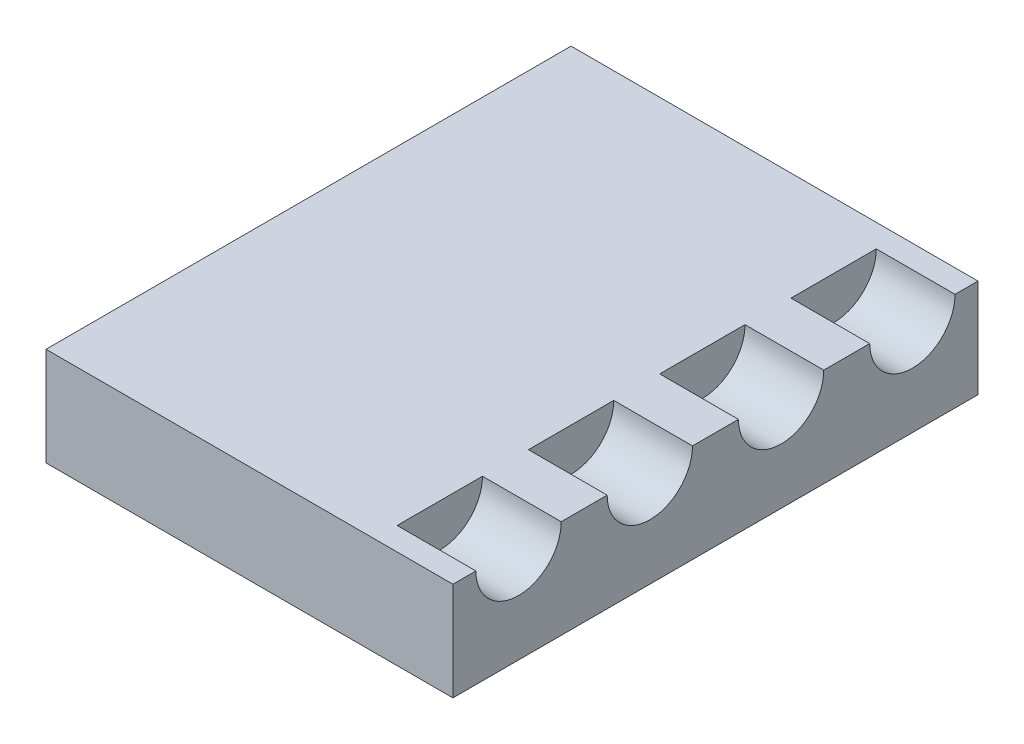
SolidWorks part; units mm, degrees
ref_plane "Front Plane" through (0, 0, 0) normal (0, 0, 1) x (1, 0, 0)
ref_plane "Top Plane" through (0, 0, 0) normal (0, 1, 0) x (1, 0, 0)
ref_plane "Right Plane" through (0, 0, 0) normal (1, 0, 0) x (0, 0, -1)
sketch "Sketch1" plane through (0, 0, 0) normal (1, 0, 0) x (0, 0, -1)
  line L0 (0, -8.0658) -> (0, 8.0658) construction
  line L1 (30, 0) -> (-30, 0) construction
  line L3 (-40, 0) -> (40, 0)
  line L4 (-40, 0) -> (-40, -15)
  line L5 (-40, -15) -> (40, -15)
  line L6 (40, 0) -> (40, -15)
  circle A0 centre (-30, 0) radius 6.5
  circle A1 centre (-10, 0) radius 6.5
  circle A2 centre (10, 0) radius 6.5
  circle A3 centre (30, 0) radius 6.5
  point P3 (10, 0)
  point P4 (0, 0)
  point P8 (0, 0)
  point P14 (-10, 0)
  point P19 (0, 0)
  dimension "D1" = 13
  dimension "D2" = 60
  dimension "D3" = 15
  dimension "D4" = 80
extrude "Boss-Extrude1" add sketch "Sketch1" along normal blind 12 contours A3 L3 A2 A1 A0 L4 L5 L6
sketch "Sketch2" plane through (0, 0, 0) normal (-1, 0, 0) x (0, 0, 1)
  line L1 (-40, -15) -> (40, -15)
  line L2 (-40, -15) -> (-40, 0)
  line L3 (-40, 0) -> (40, 0)
  line L4 (40, -15) -> (40, 0)
  point P5 (40, 0)
extrude "Boss-Extrude2" add sketch "Sketch2" along normal blind 50
